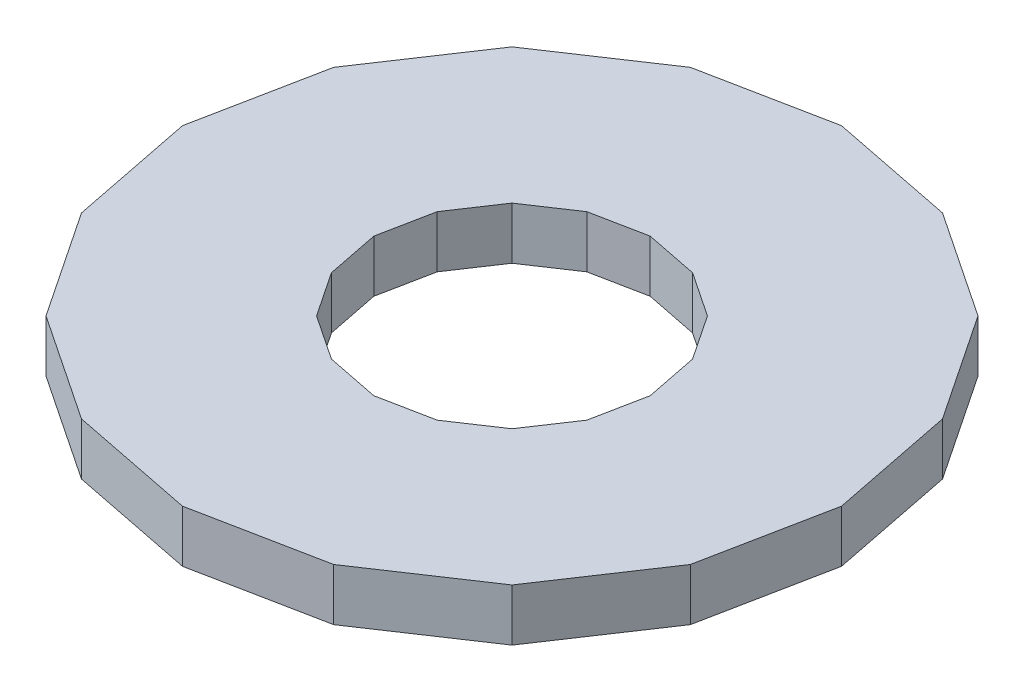
SolidWorks part; units mm, degrees
ref_plane "Front Plane" through (0, 0, 0) normal (0, 0, 1) x (1, 0, 0)
ref_plane "Top Plane" through (0, 0, 0) normal (0, 1, 0) x (1, 0, 0)
ref_plane "Right Plane" through (0, 0, 0) normal (1, 0, 0) x (0, 0, -1)
sketch "Sketch1" plane through (0, 0, 0) normal (0, 1, 0) x (1, 0, 0)
  line L1 (50.5078, 0) -> (46.6632, 19.3285)
  line L2 (46.6632, 19.3285) -> (35.7144, 35.7144)
  line L3 (35.7144, 35.7144) -> (19.3285, 46.6632)
  line L4 (19.3285, 46.6632) -> (0, 50.5078)
  line L5 (0, 50.5078) -> (-19.3285, 46.6632)
  line L6 (-19.3285, 46.6632) -> (-35.7144, 35.7144)
  line L7 (-35.7144, 35.7144) -> (-46.6632, 19.3285)
  line L8 (-46.6632, 19.3285) -> (-50.5078, 0)
  line L9 (-50.5078, 0) -> (-46.6632, -19.3285)
  line L10 (-46.6632, -19.3285) -> (-35.7144, -35.7144)
  line L11 (-35.7144, -35.7144) -> (-19.3285, -46.6632)
  line L12 (-19.3285, -46.6632) -> (0, -50.5078)
  line L13 (0, -50.5078) -> (19.3285, -46.6632)
  line L14 (19.3285, -46.6632) -> (35.7144, -35.7144)
  line L15 (35.7144, -35.7144) -> (46.6632, -19.3285)
  line L16 (46.6632, -19.3285) -> (50.5078, 0)
  line L17 (120.4314, 0) -> (111.2641, 46.0871)
  line L18 (111.2641, 46.0871) -> (85.1579, 85.1579)
  line L19 (85.1579, 85.1579) -> (46.0871, 111.2641)
  line L20 (46.0871, 111.2641) -> (0, 120.4314)
  line L21 (0, 120.4314) -> (-46.0871, 111.2641)
  line L22 (-46.0871, 111.2641) -> (-85.1579, 85.1579)
  line L23 (-85.1579, 85.1579) -> (-111.2641, 46.0871)
  line L24 (-111.2641, 46.0871) -> (-120.4314, 0)
  line L25 (-120.4314, 0) -> (-111.2641, -46.0871)
  line L26 (-111.2641, -46.0871) -> (-85.1579, -85.1579)
  line L27 (-85.1579, -85.1579) -> (-46.0871, -111.2641)
  line L28 (-46.0871, -111.2641) -> (0, -120.4314)
  line L29 (0, -120.4314) -> (46.0871, -111.2641)
  line L30 (46.0871, -111.2641) -> (85.1579, -85.1579)
  line L31 (85.1579, -85.1579) -> (111.2641, -46.0871)
  line L32 (111.2641, -46.0871) -> (120.4314, 0)
  circle A0 centre (0, 0) radius 49.5373 construction
  circle A1 centre (0, 0) radius 118.1173 construction
  dimension "D1" = 46.99
  dimension "D2" = 68.58
extrude "Boss-Extrude1" add sketch "Sketch1" along normal blind 19.05
